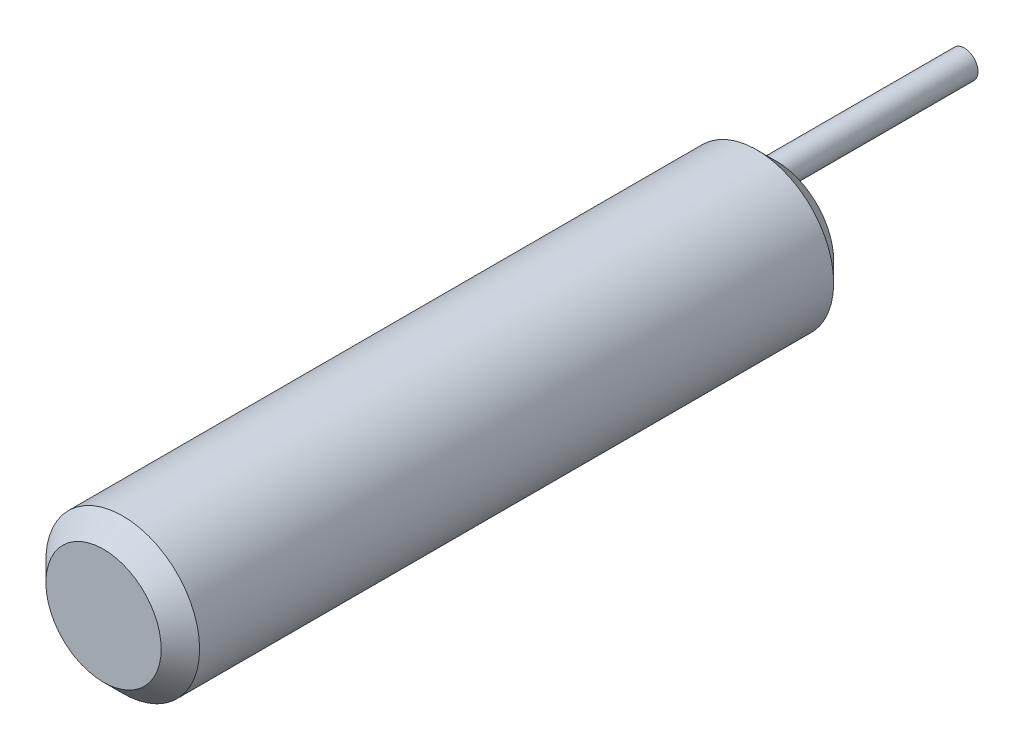
SolidWorks part; units mm, degrees
ref_plane "Спереди" through (0, 0, 0) normal (0, 0, 1) x (1, 0, 0)
ref_plane "Сверху" through (0, 0, 0) normal (0, 1, 0) x (1, 0, 0)
ref_plane "Справа" through (0, 0, 0) normal (1, 0, 0) x (0, 0, -1)
sketch "Эскиз1" plane through (0, 0, 0) normal (0, 0, 1) x (1, 0, 0)
  circle A0 centre (0, 0) radius 4
  dimension "D1" = 8
extrude "Бобышка-Вытянуть1" add sketch "Эскиз1" along normal blind 35
chamfer "Фаска1" distance 1 angle 45 1 edges at (4, 0, 35)
sketch "Эскиз2" plane through (0, 0, 0) normal (0, 0, -1) x (-1, 0, 0)
  circle A0 centre (0.2002, 2.2781) radius 0.7132
extrude "Бобышка-Вытянуть2" add sketch "Эскиз2" along normal blind 10
